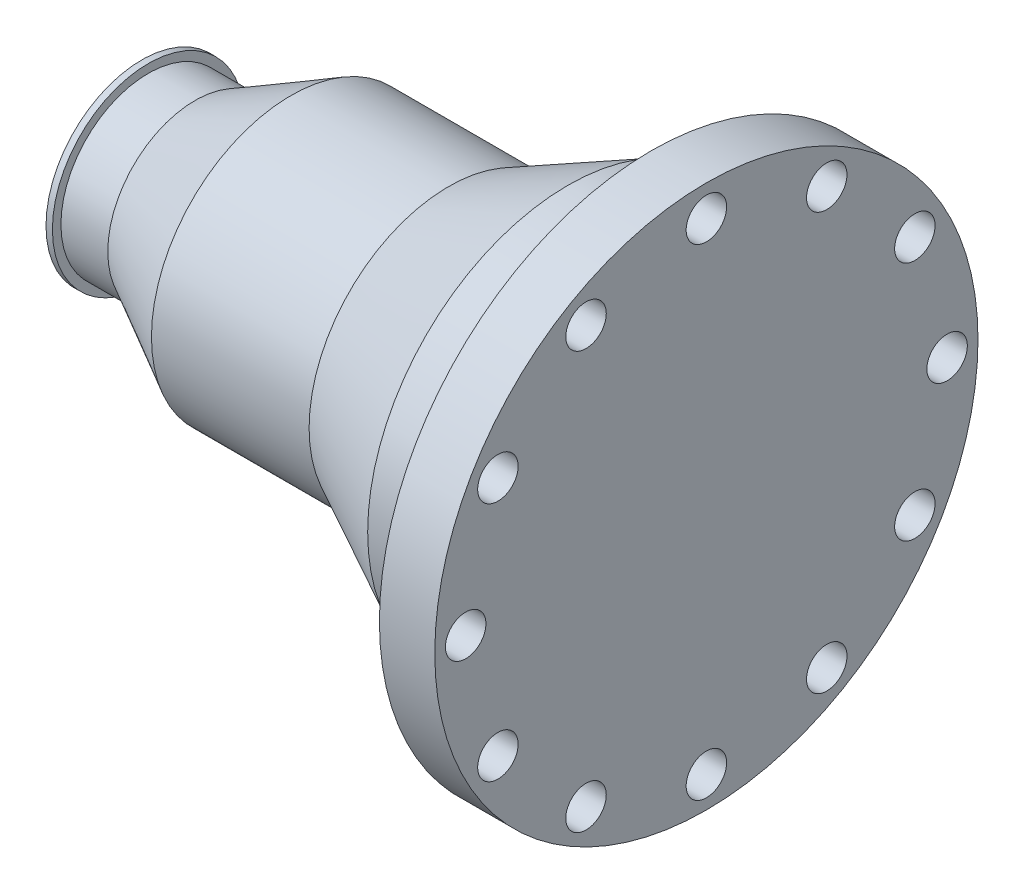
SolidWorks part; units mm, degrees
ref_plane "Спереди" through (0, 0, 0) normal (0, 0, 1) x (1, 0, 0)
ref_plane "Сверху" through (0, 0, 0) normal (0, 1, 0) x (1, 0, 0)
ref_plane "Справа" through (0, 0, 0) normal (1, 0, 0) x (0, 0, -1)
sketch "Эскиз1" plane through (0, 0, 0) normal (0, 0, 1) x (1, 0, 0)
  line L0 (0, 0) -> (265, 0)
  line L1 (0, 0) -> (0, 45)
  line L2 (0, 45) -> (3, 45)
  line L3 (3, 45) -> (3, 41)
  line L4 (3, 41) -> (25, 41)
  line L5 (25, 41) -> (70, 65.5)
  line L6 (70, 65.5) -> (144, 65.5)
  line L7 (144, 65.5) -> (200, 94)
  line L8 (200, 94) -> (220, 94)
  line L9 (220, 94) -> (220, 95)
  line L10 (220, 95) -> (239, 95)
  line L11 (239, 95) -> (239, 100)
  line L12 (239, 100) -> (239, 127.5)
  line L13 (239, 127.5) -> (265, 127.5)
  line L14 (265, 127.5) -> (265, 0)
revolve "Повернуть1" add sketch "Эскиз1" angle 360 about L0
sketch "Эскиз2" plane through (0, 0, 0) normal (0, 0, 1) x (1, 0, 0)
  line L0 (0, 0) -> (257, 0)
  line L1 (0, 0) -> (0, 31)
  line L2 (0, 45) -> (0, -45) construction
  line L3 (0, 31) -> (42, 31)
  line L4 (42, 31) -> (70, 38.5026)
  line L5 (70, 65.5) -> (70, -65.5) construction
  line L6 (90, 52.5) -> (142, 52.5)
  line L7 (143.5, 52.5) -> (146.6699, 52.5)
  line L8 (147.6699, 55) -> (200, 55)
  line L9 (200, 94) -> (200, -94) construction
  line L10 (200, 55) -> (200, 38.5026)
  line L11 (200, 38.5026) -> (220, 38.5026)
  line L12 (220, 94) -> (220, -94) construction
  line L13 (220, 38.5026) -> (220, 47)
  line L14 (220, 47) -> (239, 47)
  line L15 (239, 95) -> (239, -95) construction
  line L16 (239, 47) -> (239, 34)
  line L17 (239, 34) -> (257, 34)
  line L18 (257, 34) -> (257, 0)
  arc A0 (70, 38.5026) -> (90, 52.5) centre (107.8022, 5.7765) cw
  arc A1 (142, 52.5) -> (143.5, 52.5) centre (142.75, 49.8032) cw
  arc A2 (146.6699, 52.5) -> (147.6699, 55) centre (147.5934, 53.5806) cw
revolve "Вырез-Повернуть1" cut sketch "Эскиз2" angle 360 about L0
sketch "Эскиз3" plane through (0, 0, 0) normal (1, 0, 0) x (0, 0, -1)
  circle A0 centre (0, 113) radius 9.5
extrude "Вырез-Вытянуть1" cut sketch "Эскиз3" along normal through all
sketch "Эскиз4" plane through (0, 0, 0) normal (1, 0, 0) x (0, 0, -1)
  circle A0 centre (-56.5, 97.8609) radius 9.5
extrude "Вырез-Вытянуть2" cut sketch "Эскиз4" along normal through all
sketch "Эскиз5" plane through (0, 0, 0) normal (1, 0, 0) x (0, 0, -1)
  circle A0 centre (-97.8609, 56.5) radius 9.5
extrude "Вырез-Вытянуть3" cut sketch "Эскиз5" along normal through all
sketch "Эскиз6" plane through (0, 0, 0) normal (1, 0, 0) x (0, 0, -1)
  circle A0 centre (-113, 0) radius 9.5
extrude "Вырез-Вытянуть4" cut sketch "Эскиз6" along normal through all
sketch "Эскиз7" plane through (0, 0, 0) normal (1, 0, 0) x (0, 0, -1)
  circle A0 centre (-97.8609, -56.5) radius 9.5
extrude "Вырез-Вытянуть5" cut sketch "Эскиз7" along normal through all
sketch "Эскиз8" plane through (0, 0, 0) normal (1, 0, 0) x (0, 0, -1)
  circle A0 centre (-56.5, -97.8609) radius 9.5
extrude "Вырез-Вытянуть6" cut sketch "Эскиз8" along normal through all
sketch "Эскиз9" plane through (0, 0, 0) normal (1, 0, 0) x (0, 0, -1)
  circle A0 centre (0, -113) radius 9.5
extrude "Вырез-Вытянуть7" cut sketch "Эскиз9" along normal through all
sketch "Эскиз10" plane through (0, 0, 0) normal (1, 0, 0) x (0, 0, -1)
  circle A0 centre (56.5, -97.8609) radius 9.5
extrude "Вырез-Вытянуть8" cut sketch "Эскиз10" along normal through all
sketch "Эскиз11" plane through (0, 0, 0) normal (1, 0, 0) x (0, 0, -1)
  circle A0 centre (97.8609, -56.5) radius 9.5
extrude "Вырез-Вытянуть9" cut sketch "Эскиз11" along normal through all
sketch "Эскиз12" plane through (0, 0, 0) normal (1, 0, 0) x (0, 0, -1)
  circle A0 centre (113, 0) radius 9.5
extrude "Вырез-Вытянуть10" cut sketch "Эскиз12" along normal through all
sketch "Эскиз13" plane through (0, 0, 0) normal (1, 0, 0) x (0, 0, -1)
  circle A0 centre (97.8609, 56.5) radius 9.5
extrude "Вырез-Вытянуть11" cut sketch "Эскиз13" along normal through all
sketch "Эскиз14" plane through (0, 0, 0) normal (1, 0, 0) x (0, 0, -1)
  circle A0 centre (56.5, 97.8609) radius 9.5
extrude "Вырез-Вытянуть12" cut sketch "Эскиз14" along normal through all
